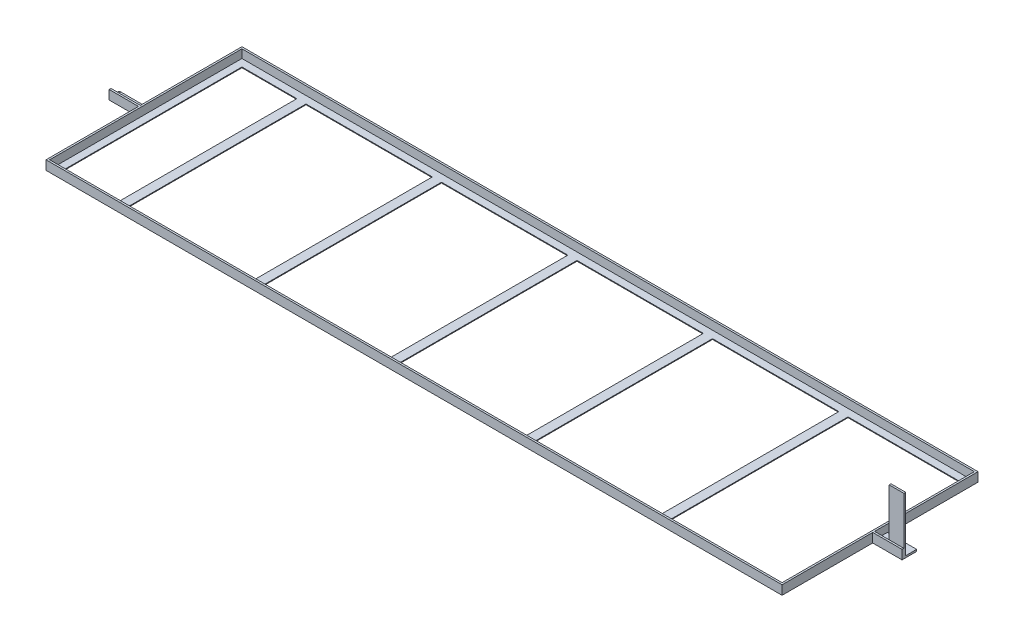
SolidWorks part; units mm, degrees
ref_plane "Front Plane" through (0, 0, 0) normal (0, 0, 1) x (1, 0, 0)
ref_plane "Top Plane" through (0, 0, 0) normal (0, 1, 0) x (1, 0, 0)
ref_plane "Right Plane" through (0, 0, 0) normal (1, 0, 0) x (0, 0, -1)
sketch "Sketch1" plane through (0, 0, 0) normal (0, 1, 0) x (1, 0, 0)
  line L0 (-610, 242.5) -> (1350, 242.5)
  line L1 (-1000, 262.5) -> (1000, 262.5)
  line L2 (-1000, 262.5) -> (-1000, -262.5)
  line L3 (-1000, -262.5) -> (1000, -262.5)
  line L4 (1000, 262.5) -> (1000, -262.5)
  line L5 (-1000, 262.5) -> (1000, -262.5) construction
  line L6 (-1000, -262.5) -> (1000, 262.5) construction
  line L7 (-980, 242.5) -> (980, 242.5)
  line L8 (-980, 242.5) -> (-980, -242.5)
  line L9 (-980, -242.5) -> (980, -242.5)
  line L10 (980, 242.5) -> (980, -242.5)
  line L11 (-980, 242.5) -> (980, -242.5) construction
  line L12 (-980, -242.5) -> (980, 242.5) construction
  line L13 (-830, 242.5) -> (-805, 242.5)
  line L14 (-830, 242.5) -> (-830, -242.5)
  line L15 (-830, -242.5) -> (-805, -242.5)
  line L16 (-805, 242.5) -> (-805, -242.5)
  line L17 (-460, 242.5) -> (-460, -242.5)
  line L18 (-460, 242.5) -> (-435, 242.5)
  line L19 (-435, 242.5) -> (-435, -242.5)
  line L20 (-460, -242.5) -> (-435, -242.5)
  line L21 (-240, 242.5) -> (1720, 242.5)
  line L22 (-90, 242.5) -> (-90, -242.5)
  line L23 (-90, 242.5) -> (-65, 242.5)
  line L24 (-65, 242.5) -> (-65, -242.5)
  line L25 (-90, -242.5) -> (-65, -242.5)
  line L26 (130, 242.5) -> (2090, 242.5)
  line L27 (280, 242.5) -> (280, -242.5)
  line L28 (280, 242.5) -> (305, 242.5)
  line L29 (305, 242.5) -> (305, -242.5)
  line L30 (280, -242.5) -> (305, -242.5)
  line L31 (500, 242.5) -> (2460, 242.5)
  line L32 (650, 242.5) -> (650, -242.5)
  line L33 (650, 242.5) -> (675, 242.5)
  line L34 (675, 242.5) -> (675, -242.5)
  line L35 (650, -242.5) -> (675, -242.5)
  point P0 (0, 0)
  point P6 (0, 0)
  dimension "D1" = 525
  dimension "D2" = 2000
  dimension "D3" = 20
  dimension "D4" = 20
  dimension "D5" = 150
  dimension "D6" = 25
  dimension "D8" = 345
  dimension "D7" = 5
extrude "Boss-Extrude1" add sketch "Sketch1" along normal blind 2
sketch "Sketch2" plane through (0, 0, 0) normal (0, 1, 0) x (1, 0, 0)
  line L1 (-1005, 267.5) -> (1005, 267.5)
  line L2 (-1005, 267.5) -> (-1005, -267.5)
  line L3 (-1005, -267.5) -> (1005, -267.5)
  line L4 (1005, 267.5) -> (1005, -267.5)
  line L5 (-1005, 267.5) -> (1005, -267.5) construction
  line L6 (-1005, -267.5) -> (1005, 267.5) construction
  line L7 (-1000, 262.5) -> (-1000, -262.5) construction
  line L9 (-1000, 262.5) -> (1000, 262.5)
  line L10 (-1000, 262.5) -> (-1000, -262.5)
  line L11 (-1000, -262.5) -> (1000, -262.5)
  line L12 (1000, 262.5) -> (1000, -262.5)
  line L13 (-1000, 262.5) -> (1000, -262.5) construction
  line L14 (-1000, -262.5) -> (1000, 262.5) construction
  point P0 (0, 0)
  point P10 (0, 0)
  dimension "D1" = 5
  dimension "D2" = 5
  dimension "D3" = 525
  dimension "D4" = 2000
extrude "Boss-Extrude2" add sketch "Sketch2" along normal blind 25
sketch "Sketch3" plane through (1005, 0, 0) normal (1, 0, 0) x (0, 0, -1)
  line L0 (-20, 25) -> (-20, 0)
  line L1 (-267.5, 25) -> (267.5, 25) construction
  line L2 (-267.5, 0) -> (267.5, 0) construction
  line L3 (-20, 0) -> (20, 0)
  line L4 (20, 0) -> (20, 5)
  line L5 (20, 5) -> (-15, 5)
  line L6 (-15, 5) -> (-15, 25)
  line L7 (-15, 25) -> (-20, 25)
  line L8 (0, 45.0501) -> (0, -31.2645) construction
  dimension "D1" = 40
  dimension "D2" = 5
  dimension "D3" = 5
extrude "Boss-Extrude3" add sketch "Sketch3" along normal blind 80
sketch "Sketch4" plane through (0, 0, 15) normal (0, 0, -1) x (-1, 0, 0)
  line L1 (-1085, 5) -> (-1045, 5)
  line L2 (-1085, 5) -> (-1085, 155)
  line L3 (-1085, 155) -> (-1045, 155)
  line L4 (-1045, 5) -> (-1045, 155)
  dimension "D1" = 40
  dimension "D2" = 150
extrude "Boss-Extrude4" add sketch "Sketch4" along normal blind 5
sketch "Sketch5" plane through (-1005, 0, 0) normal (-1, 0, 0) x (0, 0, 1)
  line L0 (0, 68.8168) -> (0, -56.8487) construction
  line L1 (15, 25) -> (15, 0)
  line L2 (-267.5, 0) -> (267.5, 0) construction
  line L3 (15, 0) -> (-15, 0)
  line L4 (-15, 0) -> (-15, 5)
  line L5 (-15, 5) -> (10, 5)
  line L6 (10, 5) -> (10, 25)
  line L7 (-267.5, 25) -> (267.5, 25) construction
  line L8 (10, 25) -> (15, 25)
  dimension "D1" = 5
  dimension "D2" = 30
  dimension "D3" = 5
extrude "Boss-Extrude5" add sketch "Sketch5" along normal blind 80
sketch "Sketch8" plane through (0, 0, 15) normal (0, 0, 1) x (1, 0, 0)
  line L0 (-1085, 0) -> (-1085, 25) construction
  line L1 (-1085, 0) -> (-1005, 0) construction
  circle A0 centre (-1077, 12.5) radius 2
  point P6 (0, 0)
  dimension "D1" = 4
  dimension "D3" = 12.5
  dimension "D2" = 8
extrude "Boss-Extrude7" add sketch "Sketch8" against normal blind 20
